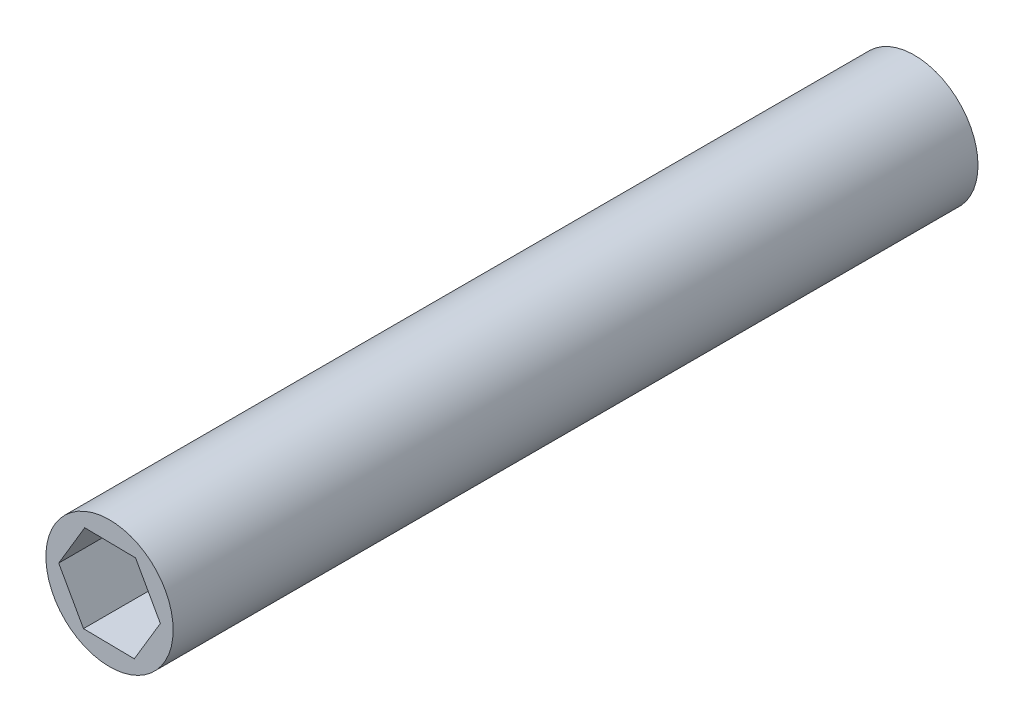
SolidWorks part; units mm, degrees
material "Cast Alloy Steel"
ref_plane "Front Plane" through (0, 0, 0) normal (0, 0, 1) x (1, 0, 0)
ref_plane "Top Plane" through (0, 0, 0) normal (0, 1, 0) x (1, 0, 0)
ref_plane "Right Plane" through (0, 0, 0) normal (1, 0, 0) x (0, 0, -1)
sketch "Sketch2" plane through (0, 0, 0) normal (0, 0, 1) x (1, 0, 0)
  line L1 (0.6626, -12.8194) -> (11.4332, -5.8358)
  line L2 (11.4332, -5.8358) -> (10.7706, 6.9835)
  line L3 (10.7706, 6.9835) -> (-0.6626, 12.8194)
  line L4 (-0.6626, 12.8194) -> (-11.4332, 5.8358)
  line L5 (-11.4332, 5.8358) -> (-10.7706, -6.9835)
  line L6 (-10.7706, -6.9835) -> (0.6626, -12.8194)
  circle A0 centre (0, 0) radius 11.1167 construction
  circle A1 centre (0, 0) radius 16.0527
  dimension "D1" = 12.8194
extrude "Boss-Extrude1" add sketch "Sketch2" against normal blind 203 contours A1
sketch "Sketch5" plane through (0, 0, 0) normal (0, 0, 1) x (1, 0, 0)
  line L1 (6.2495, -11.1929) -> (12.8181, -0.1842)
  line L2 (12.8181, -0.1842) -> (6.5686, 11.0087)
  line L3 (6.5686, 11.0087) -> (-6.2495, 11.1929)
  line L4 (-6.2495, 11.1929) -> (-12.8181, 0.1842)
  line L5 (-12.8181, 0.1842) -> (-6.5686, -11.0087)
  line L6 (-6.5686, -11.0087) -> (6.2495, -11.1929)
  circle A0 centre (0, 0) radius 11.1019 construction
  dimension "D1" = 12.8194
extrude "Cut-Extrude1" cut sketch "Sketch5" against normal blind 476 contours L2 L3 L4 L5 L6 L1
